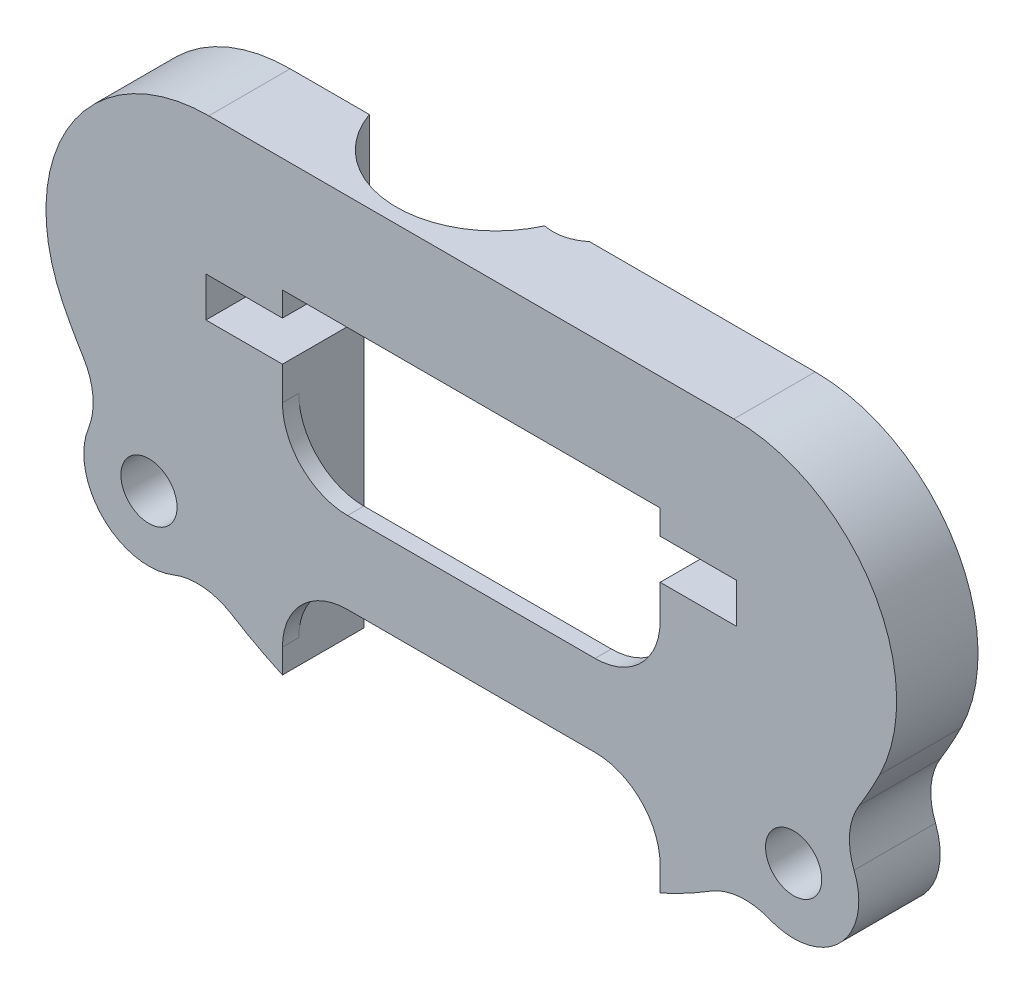
SolidWorks part; units mm, degrees
material "ABS"
ref_plane "Front Plane" through (0, 0, 0) normal (0, 0, 1) x (1, 0, 0)
ref_plane "Top Plane" through (0, 0, 0) normal (0, 1, 0) x (1, 0, 0)
ref_plane "Right Plane" through (0, 0, 0) normal (1, 0, 0) x (0, 0, -1)
sketch "Sketch1" plane through (0, 0, 0) normal (0, 0, 1) x (1, 0, 0)
  line L0 (0, 0) -> (0, -28) construction
  line L1 (-27.9285, 2) -> (27.9285, 2)
  line L2 (-28, 0) -> (28, 0) construction
  line L3 (-11.6, -25.4841) -> (-11.6, -8.95)
  line L4 (-11.6, -8.95) -> (-16.3, -8.95)
  line L5 (-16.3, -8.95) -> (-16.3, -6.5)
  line L6 (-16.3, -6.5) -> (-11.6, -6.5)
  line L7 (-11.6, -6.5) -> (-11.6, -5)
  line L8 (-11.6, -5) -> (11.6, -5)
  line L9 (11.6, -5) -> (11.6, -6.5)
  line L10 (11.6, -6.5) -> (16.3, -6.5)
  line L11 (16.3, -6.5) -> (16.3, -8.95)
  line L12 (16.3, -8.95) -> (11.6, -8.95)
  line L13 (11.6, -8.95) -> (11.6, -25.4841)
  line L14 (0, 0) -> (-19.799, -19.799) construction
  line L15 (0, 0) -> (19.799, -19.799) construction
  arc A0 (22.4182, -16.7758) -> (27.9285, 2) centre (0, 0) ccw
  arc A1 (-22.4182, -16.7758) -> (-27.9285, 2) centre (0, 0) cw
  circle A3 centre (-19.799, -19.799) radius 1.725
  circle A4 centre (19.799, -19.799) radius 1.725
  arc A7 (-22.4182, -16.7758) -> (-16.7758, -22.4182) centre (-19.799, -19.799) ccw
  arc A8 (16.7758, -22.4182) -> (22.4182, -16.7758) centre (19.799, -19.799) ccw
  arc A11 (-16.7758, -22.4182) -> (-11.6, -25.4841) centre (0, 0) ccw
  arc A12 (-28, 0) -> (28, 0) centre (0, 0) ccw construction
  arc A14 (11.6, -25.4841) -> (16.7758, -22.4182) centre (0, 0) ccw
  dimension "D1" = 23.2
  dimension "D3" = 3.45
  dimension "D4" = 4
  dimension "D5" = 28
  dimension "D6" = 5
  dimension "D7" = 2.45
  dimension "D2" = 45
  dimension "D8" = 4.7
  dimension "D9" = 1.5
  dimension "D10" = 2
extrude "Boss-Extrude1" add sketch "Sketch1" along normal blind 5
sketch "Sketch5" plane through (0, 2, 0) normal (0, 1, 0) x (1, 0, 0)
  line L1 (-11.6, -5) -> (-11.6, 0) construction
  line L2 (-11.6, -5) -> (-11.6, 0) construction
  line L3 (27.9285, 0) -> (-27.9285, 0) construction
  arc A0 (0.0459, 4.5403) -> (0.0459, -0.5403) centre (-5.5, 2) ccw
  arc A1 (0.0459, -0.5403) -> (0.0459, 4.5403) centre (0.6, 2) ccw
  point P1 (0, 0)
  dimension "D1" = 12.2
  dimension "D2" = 5.2
  dimension "D3" = 2
extrude "Cut-Extrude3" cut sketch "Sketch5" against normal up to next
sketch "Sketch6" plane through (0, 0, 5) normal (0, 0, 1) x (1, 0, 0)
  line L0 (-11.6, -25.4841) -> (-11.6, -8.95) construction
  line L1 (-11.6, -15) -> (11.6, -15)
  line L2 (-11.6, -15) -> (-11.6, -20)
  line L3 (-11.6, -20) -> (11.6, -20)
  line L4 (11.6, -15) -> (11.6, -20)
  line L5 (11.6, -8.95) -> (11.6, -25.4841) construction
  dimension "D1" = 15
  dimension "D2" = 5
extrude "Boss-Extrude2" add sketch "Sketch6" against normal blind 1
sketch "Sketch7" plane through (0, 0, 0) normal (0, 0, -1) x (-1, 0, 0)
  line L1 (-16.699, -21.5888) -> (-16.699, -18.0092)
  line L2 (-16.699, -18.0092) -> (-19.799, -16.2194)
  line L3 (-19.799, -16.2194) -> (-22.899, -18.0092)
  line L4 (-22.899, -18.0092) -> (-22.899, -21.5888)
  line L5 (-22.899, -21.5888) -> (-19.799, -23.3786)
  line L6 (-19.799, -23.3786) -> (-16.699, -21.5888)
  line L7 (22.899, -18.0092) -> (19.799, -16.2194)
  line L8 (19.799, -16.2194) -> (16.699, -18.0092)
  line L9 (16.699, -18.0092) -> (16.699, -21.5888)
  line L10 (16.699, -21.5888) -> (19.799, -23.3786)
  line L11 (19.799, -23.3786) -> (22.899, -21.5888)
  line L12 (22.899, -21.5888) -> (22.899, -18.0092)
  circle A0 centre (-19.799, -19.799) radius 3.1 construction
  circle A1 centre (19.799, -19.799) radius 3.1 construction
  dimension "D1" = 6.2
extrude "Cut-Extrude4" cut sketch "Sketch7" against normal blind 2
fillet "Fillet1" radius 4 8 edges at (-22.4182, -16.7758, 2.5) (-16.7758, -22.4182, 2.5) (22.4182, -16.7758, 2.5) (16.7758, -22.4182, 2.5) (-11.6, -20, 4.5) (-11.6, -15, 4.5) (11.6, -15, 4.5) (11.6, -20, 4.5)
fillet "Fillet2" radius 10 2 edges at (-27.9285, 2, 2.5) (27.9285, 2, 2.5)
equation "\"D3@Sketch1\"=3.00mm+\"print_free@Parameters@FabricationParameters.sldprt\""
equation "\"D1@Sketch1\"=23.00mm+\"print_fit@Parameters@FabricationParameters.sldprt\""
equation "\"D7@Sketch1\"=2.00mm+\"print_free@Parameters@FabricationParameters.sldprt\""
equation "\"D8@Sketch1\"=4.50mm+\"print_fit@Parameters@FabricationParameters.sldprt\""
equation "\"D1@Sketch7\"=6mm+\"print_fit@Parameters@FabricationParameters.sldprt\""
equation "\"D1@Sketch5\"=12.00mm+\"print_fit@Parameters@FabricationParameters.sldprt\""
equation "\"D2@Sketch5\"=5mm+\"print_fit@Parameters@FabricationParameters.sldprt\""
